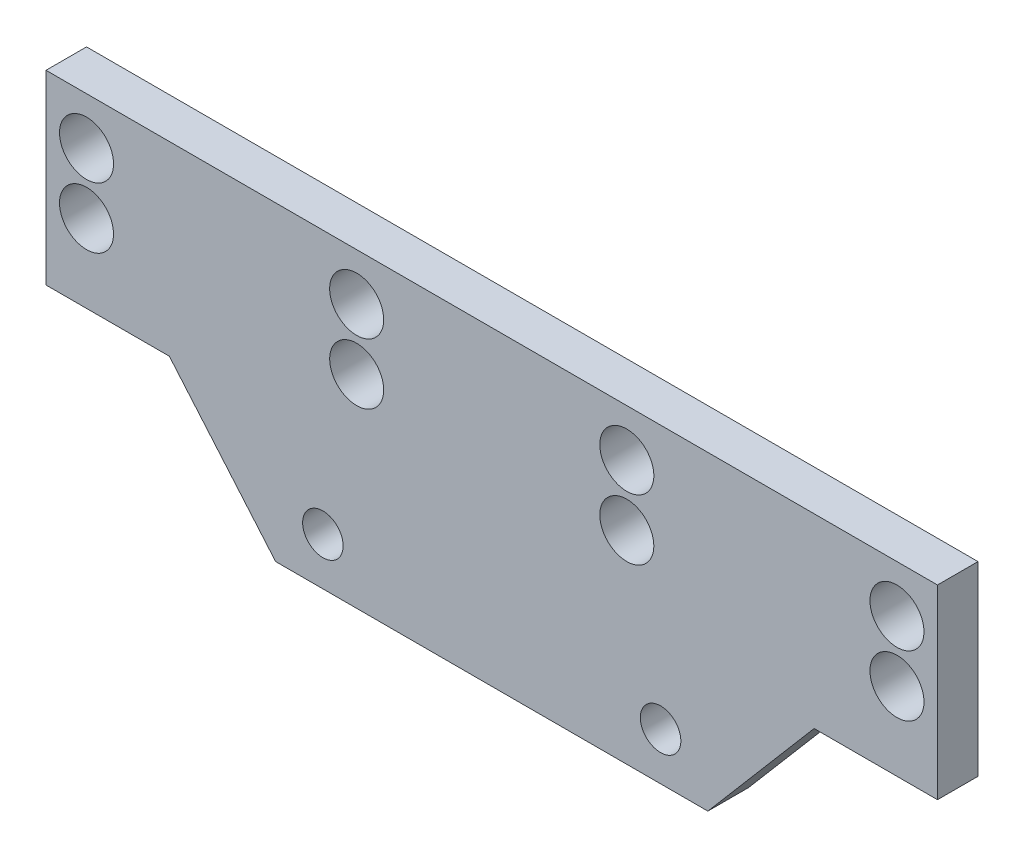
SolidWorks part; units mm, degrees
ref_plane "前视基准面" through (0, 0, 0) normal (0, 0, 1) x (1, 0, 0)
ref_plane "上视基准面" through (0, 0, 0) normal (0, 1, 0) x (1, 0, 0)
ref_plane "右视基准面" through (0, 0, 0) normal (1, 0, 0) x (0, 0, -1)
sketch "草图1" plane through (0, 0, 0) normal (0, 0, 1) x (1, 0, 0)
  line L0 (4.3498, 25.4773) -> (4.3498, 2.4773) construction
  line L1 (-28.6502, 25.4773) -> (37.3498, 25.4773)
  line L2 (-28.6502, 25.4773) -> (-28.6502, 2.4773)
  line L3 (-28.6502, 2.4773) -> (37.3498, 2.4773)
  line L4 (37.3498, 25.4773) -> (37.3498, 2.4773)
  line L5 (-28.6502, 25.4773) -> (37.3498, 2.4773) construction
  line L6 (-28.6502, 2.4773) -> (37.3498, 25.4773) construction
  line L7 (-44.3591, 21.9773) -> (44.5513, 21.9773) construction
  line L8 (-44.3591, 19.7273) -> (44.5513, 19.7273) construction
  circle A0 centre (-5.6502, 21.9773) radius 2
  circle A1 centre (-25.6502, 21.9773) radius 2
  circle A2 centre (14.3498, 21.9773) radius 2
  circle A3 centre (34.3498, 21.9773) radius 2
  circle A4 centre (34.3498, 17.4773) radius 2
  circle A5 centre (14.3498, 17.4773) radius 2
  circle A6 centre (-5.6502, 17.4773) radius 2
  circle A7 centre (-25.6502, 17.4773) radius 2
  circle A8 centre (-8.1502, 5.9773) radius 1.5
  circle A9 centre (16.8498, 5.9773) radius 1.5
  point P0 (4.3498, 13.9773)
  dimension "D3" = 4
  dimension "D4" = 4
  dimension "D5" = 20
  dimension "D6" = 20
  dimension "D7" = 3.5
  dimension "D8" = 4.5
  dimension "D9" = 25
  dimension "D10" = 3.5
  dimension "D11" = 3
  dimension "D1" = 23
  dimension "D2" = 66
extrude "凸台-拉伸1" add sketch "草图1" along normal blind 3
sketch "草图2" plane through (0, 0, 3) normal (0, 0, 1) x (1, 0, 0)
  line L0 (4.3498, 25.4773) -> (4.3498, 2.4773) construction
  line L1 (37.3498, 25.4773) -> (-28.6502, 25.4773) construction
  line L2 (-28.6502, 2.4773) -> (37.3498, 2.4773) construction
  line L3 (-28.6502, 11.7078) -> (-19.5175, 11.7078)
  line L4 (-28.6502, 25.4773) -> (-28.6502, 2.4773) construction
  line L5 (-19.5175, 11.7078) -> (-11.6502, 2.4773)
  line L6 (-11.6502, 2.4773) -> (-28.6502, 2.4773)
  line L7 (-28.6502, 2.4773) -> (-28.6502, 11.7078)
  line L8 (20.3498, 2.4773) -> (37.3498, 2.4773)
  line L9 (28.2172, 11.7078) -> (20.3498, 2.4773)
  line L10 (37.3498, 11.7078) -> (28.2172, 11.7078)
  line L11 (37.3498, 2.4773) -> (37.3498, 11.7078)
  dimension "D1" = 32
extrude "切除-拉伸1" cut sketch "草图2" against normal through all
